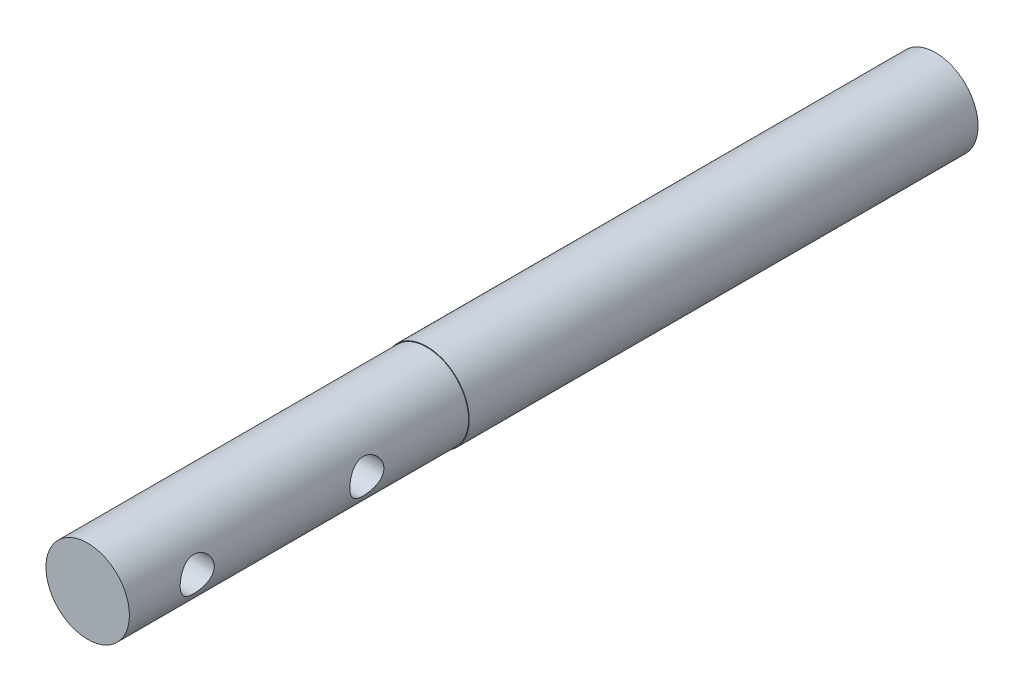
SolidWorks part; units mm, degrees
material "AISI 304"
ref_plane "Front Plane" through (0, 0, 0) normal (0, 0, 1) x (1, 0, 0)
ref_plane "Top Plane" through (0, 0, 0) normal (0, 1, 0) x (1, 0, 0)
ref_plane "Right Plane" through (0, 0, 0) normal (1, 0, 0) x (0, 0, -1)
sketch "Sketch1" plane through (0, 0, 0) normal (0, 0, 1) x (1, 0, 0)
  circle A0 centre (0, 0) radius 25
  dimension "D1" = 50
extrude "Boss-Extrude1" add sketch "Sketch1" along normal mid plane 500
sketch "Sketch2" plane through (0, 0, 0) normal (1, 0, 0) x (0, 0, -1)
  line L0 (-250, 0) -> (0, 0) construction
  line L1 (-250, 25) -> (-250, -25) construction
  line L2 (250, -25) -> (250, 25) construction
  circle A0 centre (-210, 0) radius 10.05
  circle A1 centre (-110, 0) radius 10.05
  dimension "D1" = 20.1
  dimension "D3" = 100
  dimension "D2" = 360
extrude "Cut-Extrude1" cut sketch "Sketch2" against normal through all both and the other way through all
sketch "Sketch3" plane through (0, 0, 250) normal (0, 0, 1) x (1, 0, 0)
  circle A0 centre (0, 0) radius 24.61
  dimension "D1" = 49.22
extrude "Cut-Extrude2" cut sketch "Sketch3" against normal blind 200 flip side to cut
